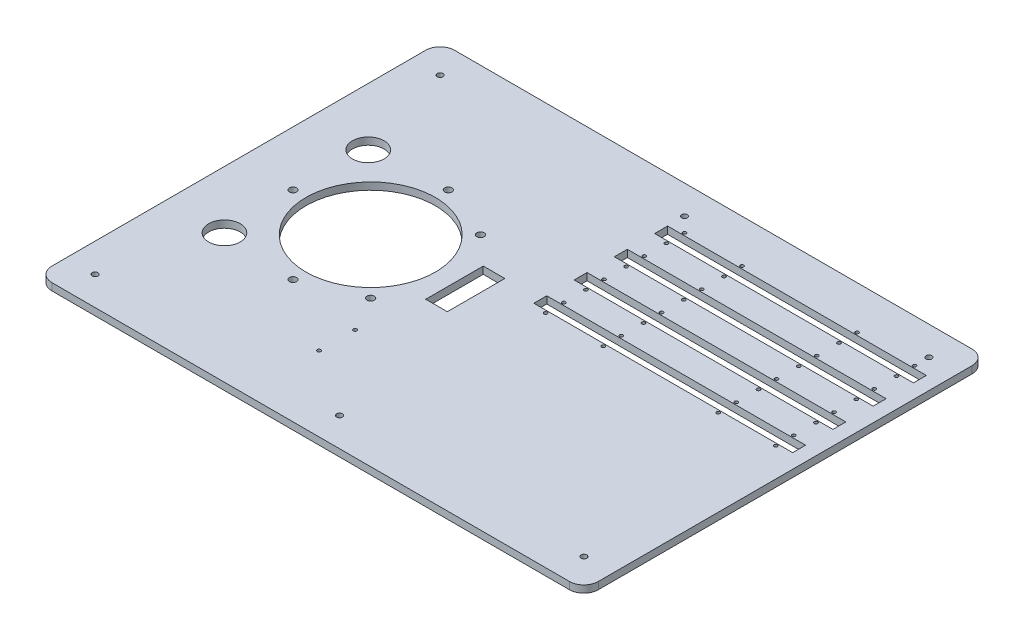
SolidWorks part; units mm, degrees
ref_plane "Front" through (0, 0, 0) normal (0, 0, 1) x (1, 0, 0)
ref_plane "Top" through (0, 0, 0) normal (0, 1, 0) x (1, 0, 0)
ref_plane "Right" through (0, 0, 0) normal (1, 0, 0) x (0, 0, -1)
sketch "Sketch1" plane through (0, 0, 0) normal (0, 1, 0) x (1, 0, 0)
  line L1 (0, 0) -> (482.6, 0)
  line L2 (0, 0) -> (0, 355.6)
  line L3 (0, 355.6) -> (482.6, 355.6)
  line L4 (482.6, 0) -> (482.6, 355.6)
  dimension "D1" = 482.6
  dimension "D2" = 355.6
extrude "Boss-Extrude1" add sketch "Sketch1" along normal blind 6.35
sketch "Sketch2" plane through (0, 6.35, 0) normal (0, 1, 0) x (1, 0, 0)
  line L0 (482.6, 355.6) -> (0, 355.6) construction
  line L1 (0, 355.6) -> (0, 0) construction
  line L2 (482.6, 0) -> (482.6, 355.6) construction
  line L3 (0, 0) -> (482.6, 0) construction
  circle A0 centre (25.4, 330.2) radius 2.55
  circle A1 centre (241.3, 330.2) radius 2.55
  circle A2 centre (457.2, 330.2) radius 2.55
  circle A3 centre (241.3, 25.4) radius 2.55
  circle A4 centre (457.2, 25.4) radius 2.55
  circle A5 centre (25.4, 25.4) radius 2.55
  dimension "D1" = 5.1
  dimension "D2" = 25.4
  dimension "D3" = 25.4
  dimension "D6" = 25.4
  dimension "D7" = 25.4
  dimension "D4" = 3
  dimension "D5" = 2
extrude "Cut-Extrude1" cut sketch "Sketch2" against normal through all
fillet "Fillet1" radius 12.7 4 edges at (0, 3.175, -355.6) (482.6, 3.175, -355.6) (482.6, 3.175, 0) (0, 3.175, 0)
sketch "Sketch3" [suppressed] plane through (0, 6.35, 0) normal (0, 1, 0) x (1, 0, 0)
  line L0 (12.7, 0) -> (469.9, 0) construction
  line L1 (482.6, 12.7) -> (482.6, 342.9) construction
  circle A0 centre (25.4, 330.2) radius 7.62
  circle A1 centre (241.3, 330.2) radius 7.62
  circle A2 centre (457.2, 330.2) radius 7.62
  circle A3 centre (241.3, 25.4) radius 7.62
  circle A4 centre (457.2, 25.4) radius 7.62
  circle A5 centre (25.4, 25.4) radius 7.62
  dimension "D1" = 15.24
  dimension "D4" = 25.4
  dimension "D5" = 25.4
  dimension "D2" = 3
  dimension "D3" = 2
extrude "Cut-Extrude2" [suppressed] cut sketch "Sketch3" against normal through all
sketch "Sketch4" [suppressed] plane through (0, 6.35, 0) normal (0, 1, 0) x (1, 0, 0)
  line L0 (482.6, 12.7) -> (482.6, 342.9) construction
  line L1 (257.81, 184.15) -> (425.45, 184.15)
  line L2 (257.81, 184.15) -> (257.81, 19.05)
  line L4 (425.45, 184.15) -> (425.45, 19.05)
  line L5 (12.7, 0) -> (469.9, 0) construction
  line L6 (257.81, 19.05) -> (425.45, 19.05)
  line L11 (469.9, 355.6) -> (12.7, 355.6) construction
  line L12 (334.01, 19.05) -> (349.25, 19.05)
  line L13 (334.01, 19.05) -> (334.01, 0)
  line L14 (334.01, 0) -> (349.25, 0)
  line L15 (349.25, 19.05) -> (349.25, 0)
  dimension "D1" = 167.64
  dimension "D2" = 165.1
  dimension "D3" = 57.15
  dimension "D4" = 76.2
  dimension "D5" = 76.2
  dimension "D6" = 171.45
extrude "Cut-Extrude3" [suppressed] cut sketch "Sketch4" against normal through all
sketch "Sketch5" plane through (0, 6.35, 0) normal (0, 1, 0) x (1, 0, 0)
  line L0 (482.6, 12.7) -> (482.6, 342.9) construction
  line L1 (469.9, 355.6) -> (12.7, 355.6) construction
  circle A0 centre (254, 317.5) radius 1.5
  circle A1 centre (304.8, 317.5) radius 1.5
  circle A3 centre (406.4, 317.5) radius 1.5
  circle A4 centre (457.2, 317.5) radius 1.5
  circle A6 centre (304.8, 301.498) radius 1.5
  circle A8 centre (406.4, 301.498) radius 1.5
  circle A9 centre (457.2, 301.498) radius 1.5
  circle A11 centre (254, 301.498) radius 1.5
  circle A12 centre (355.6, 317.5) radius 1.5 [skipped]
  circle A13 centre (355.6, 301.498) radius 1.5 [skipped]
  dimension "D1" = 3
  dimension "D4" = 228.6
  dimension "D5" = 16.002
  dimension "D6" = 38.1
  dimension "D2" = 5
  dimension "D3" = 2
extrude "Cut-Extrude4" cut sketch "Sketch5" against normal through all
sketch "Sketch6" plane through (0, 6.35, 0) normal (0, 1, 0) x (1, 0, 0)
  line L0 (482.6, 12.7) -> (482.6, 342.9) construction
  line L1 (472.44, 197.7) -> (441.44, 197.7)
  line L2 (472.44, 197.7) -> (472.44, 266.7)
  line L3 (472.44, 266.7) -> (441.44, 266.7)
  line L4 (441.44, 197.7) -> (441.44, 266.7)
  line L5 (472.44, 117.9) -> (472.44, 186.9)
  line L6 (472.44, 117.9) -> (441.44, 117.9)
  line L7 (441.44, 117.9) -> (441.44, 186.9)
  line L8 (472.44, 186.9) -> (441.44, 186.9)
  line L9 (472.44, 38.1) -> (472.44, 107.1)
  line L10 (472.44, 38.1) -> (441.44, 38.1)
  line L11 (441.44, 38.1) -> (441.44, 107.1)
  line L12 (472.44, 107.1) -> (441.44, 107.1)
  line L17 (469.9, 355.6) -> (12.7, 355.6) construction
  line L19 (472.44, -41.7) -> (472.44, 27.3) [skipped]
  line L20 (472.44, 27.3) -> (441.44, 27.3) [skipped]
  line L21 (441.44, -41.7) -> (441.44, 27.3) [skipped]
  line L22 (472.44, -41.7) -> (441.44, -41.7) [skipped]
  line L23 (12.7, 0) -> (469.9, 0) construction
  dimension "D1" = 10.16
  dimension "D2" = 69
  dimension "D3" = 31
  dimension "3.75" = 88.9
  dimension "D6" = 38.1
  dimension "D4" = 4
extrude "Cut-Extrude5" [suppressed] cut sketch "Sketch6" against normal through all
sketch "Sketch8" plane through (0, 6.35, 0) normal (0, 1, 0) x (1, 0, 0)
  line L0 (0, 342.9) -> (0, 12.7) construction
  line L1 (190.5, 203.2) -> (209.55, 203.2)
  line L2 (190.5, 203.2) -> (190.5, 152.4)
  line L3 (190.5, 152.4) -> (209.55, 152.4)
  line L4 (209.55, 203.2) -> (209.55, 152.4)
  point P6 (0, 177.8)
  point P7 (190.5, 177.8)
  dimension "D1" = 50.8
  dimension "D2" = 19.05
  dimension "D3" = 190.5
extrude "Cut-Extrude7" cut sketch "Sketch8" against normal mid plane 127
sketch "Sketch10" plane through (0, 6.35, 0) normal (0, 1, 0) x (1, 0, 0)
  line L0 (0, 342.9) -> (0, 12.7) construction
  line L1 (20.8788, 301.9425) -> (224.1042, 301.9425)
  line L2 (20.8788, 301.9425) -> (20.8788, 297.4467)
  line L3 (20.8788, 297.4467) -> (224.1042, 297.4467)
  line L4 (224.1042, 301.9425) -> (224.1042, 297.4467)
  line L5 (25.4, 297.4467) -> (29.8958, 297.4467)
  line L6 (25.4, 297.4467) -> (25.4, 58.1533)
  line L7 (25.4, 58.1533) -> (29.8958, 58.1533)
  line L8 (29.8958, 297.4467) -> (29.8958, 58.1533)
  line L13 (20.8788, 58.1533) -> (224.1042, 58.1533)
  line L14 (20.8788, 58.1533) -> (20.8788, 53.6575)
  line L15 (20.8788, 53.6575) -> (224.1042, 53.6575)
  line L16 (224.1042, 58.1533) -> (224.1042, 53.6575)
  line L17 (215.0872, 297.4467) -> (219.583, 297.4467)
  line L18 (215.0872, 297.4467) -> (215.0872, 58.1533)
  line L19 (215.0872, 58.1533) -> (219.583, 58.1533)
  line L20 (219.583, 297.4467) -> (219.583, 58.1533)
  line L22 (109.7915, 301.9425) -> (135.1915, 301.9425)
  line L23 (109.7915, 301.9425) -> (109.7915, 297.4467)
  line L24 (109.7915, 297.4467) -> (135.1915, 297.4467)
  line L25 (135.1915, 301.9425) -> (135.1915, 297.4467)
  line L26 (215.0872, 165.1) -> (219.583, 165.1)
  line L27 (215.0872, 165.1) -> (215.0872, 190.5)
  line L28 (215.0872, 190.5) -> (219.583, 190.5)
  line L29 (219.583, 165.1) -> (219.583, 190.5)
  line L30 (109.7915, 58.1533) -> (135.1915, 58.1533)
  line L31 (109.7915, 58.1533) -> (109.7915, 53.6575)
  line L32 (109.7915, 53.6575) -> (135.1915, 53.6575)
  line L33 (135.1915, 58.1533) -> (135.1915, 53.6575)
  line L34 (25.4, 165.1) -> (29.8958, 165.1)
  line L35 (25.4, 165.1) -> (25.4, 190.5)
  line L36 (25.4, 190.5) -> (29.8958, 190.5)
  line L37 (29.8958, 165.1) -> (29.8958, 190.5)
  point P16 (25.4, 177.8)
  point P19 (0, 177.8)
  point P36 (25.4, 177.8)
  point P37 (29.8958, 177.8)
  point P38 (29.8958, 177.8)
  point P39 (122.4915, 301.9425)
  point P40 (122.4915, 301.9425)
  dimension "D1" = 248.285
  dimension "D2" = 194.183
  dimension "D3" = 4.5212
  dimension "D4" = 4.5212
  dimension "D5" = 4.5212
  dimension "D6" = 4.5212
  dimension "D7" = 4.4958
  dimension "D8" = 25.4
  dimension "D9" = 25.4
extrude "Cut-Extrude9" cut sketch "Sketch10" against normal blind 6.35 contours L31 L13 L7 L14 L15 | L34 L6 L7 L8 | L23 L1 L2 L3 | L1 L25 L3 L4 | L18 L28 L20 L3 | L26 L18 L13 L20 | L13 L33 L15 L16
sketch "Sketch11" plane through (0, 6.35, 0) normal (0, 1, 0) x (1, 0, 0)
  line L0 (469.9, 355.6) -> (12.7, 355.6) construction
  line L1 (162.2, 88.9) -> (203.2, 88.9)
  line L2 (162.2, 88.9) -> (162.2, 74.9)
  line L3 (162.2, 74.9) -> (203.2, 74.9)
  line L4 (203.2, 88.9) -> (203.2, 74.9)
  line L5 (482.6, 12.7) -> (482.6, 342.9) construction
  dimension "D3" = 266.7
  dimension "D1" = 41
  dimension "D2" = 14
  dimension "D4" = 279.4
extrude "Cut-Extrude10" [suppressed] cut sketch "Sketch11" against normal through all
sketch "Sketch12" plane through (0, 6.35, 0) normal (0, 1, 0) x (1, 0, 0)
  line L0 (0, 342.9) -> (0, 12.7) construction
  line L1 (50.8, 241.3) -> (50.8, 114.3) construction
  line L3 (63.6988, 246.7424) -> (76.3988, 246.7424)
  line L4 (63.6988, 246.7424) -> (63.6988, 235.8576)
  line L5 (63.6988, 235.8576) -> (76.3988, 235.8576)
  line L6 (76.3988, 246.7424) -> (76.3988, 235.8576)
  line L7 (63.6988, 119.7424) -> (76.3988, 119.7424)
  line L8 (63.6988, 119.7424) -> (63.6988, 108.8576)
  line L9 (63.6988, 108.8576) -> (76.3988, 108.8576)
  line L10 (76.3988, 119.7424) -> (76.3988, 108.8576)
  circle A0 centre (50.8, 241.3) radius 14
  circle A1 centre (50.8, 114.3) radius 14
  point P2 (50.8, 177.8)
  point P5 (0, 177.8)
  point P17 (63.6988, 241.3)
  point P18 (63.6988, 114.3)
  dimension "D1" = 28
  dimension "D2" = 127
  dimension "D3" = 50.8
  dimension "D4" = 12.7
extrude "Cut-Extrude11" cut sketch "Sketch12" against normal mid plane 127
sketch "Sketch13" plane through (0, 6.35, 0) normal (0, 1, 0) x (1, 0, 0)
  line L1 (11.0927, 314.0237) -> (231.0973, 314.0237)
  line L2 (11.0927, 314.0237) -> (11.0927, 49.9586)
  line L3 (11.0927, 49.9586) -> (231.0973, 49.9586)
  line L4 (231.0973, 314.0237) -> (231.0973, 49.9586)
extrude "Boss-Extrude2" add sketch "Sketch13" against normal blind 6.35
sketch "Sketch14" plane through (0, 6.35, 0) normal (0, 1, 0) x (1, 0, 0)
  line L0 (29.8958, 297.4467) -> (29.8958, 58.1533) construction
  line L4 (109.7915, 53.6575) -> (135.1915, 53.6575) construction
  line L5 (0, 342.9) -> (0, 12.7) construction
  circle A0 centre (116.84, 177.8) radius 57.2135
  point P4 (29.8958, 177.8)
  dimension "D1" = 116.84
  dimension "D2" = 114.427
extrude "Cut-Extrude12" [suppressed] cut sketch "Sketch14" against normal through all
sketch "Sketch15" plane through (0, 6.35, 0) normal (0, 1, 0) x (1, 0, 0)
  line L0 (50.8, 241.3) -> (50.8, 114.3) construction
  line L1 (0, 342.9) -> (0, 12.7) construction
  circle A0 centre (50.8, 241.3) radius 13.97
  circle A1 centre (50.8, 114.3) radius 13.97
  point P6 (0, 177.8)
  point P7 (50.8, 177.8)
  dimension "D1" = 27.94
  dimension "D2" = 127
  dimension "D3" = 50.8
extrude "Cut-Extrude13" cut sketch "Sketch15" against normal through all
sketch "Sketch16" [suppressed] plane through (0, 6.35, 0) normal (0, 1, 0) x (1, 0, 0)
  line L1 (432.299, 273.4014) -> (473.1365, 273.4014)
  line L2 (432.299, 273.4014) -> (432.299, 196.3719)
  line L3 (432.299, 196.3719) -> (473.1365, 196.3719)
  line L4 (473.1365, 273.4014) -> (473.1365, 196.3719)
extrude "Boss-Extrude3" [suppressed] add sketch "Sketch16" against normal up to surface (6.35 mm away)
pattern_linear "LPattern1" count 4 spacing 35.56 along (0, 0, 1) of "Cut-Extrude4"
sketch "Sketch17" plane through (0, 6.35, 0) normal (0, 1, 0) x (1, 0, 0)
  line L1 (241.3, 315.214) -> (469.9, 315.214)
  line L2 (241.3, 315.214) -> (241.3, 303.784)
  line L3 (241.3, 303.784) -> (469.9, 303.784)
  line L4 (469.9, 315.214) -> (469.9, 303.784)
  line L5 (241.3, 279.654) -> (241.3, 268.224)
  line L6 (241.3, 279.654) -> (469.9, 279.654)
  line L7 (469.9, 279.654) -> (469.9, 268.224)
  line L8 (241.3, 268.224) -> (469.9, 268.224)
  line L9 (241.3, 244.094) -> (241.3, 232.664)
  line L10 (241.3, 244.094) -> (469.9, 244.094)
  line L11 (469.9, 244.094) -> (469.9, 232.664)
  line L12 (241.3, 232.664) -> (469.9, 232.664)
  line L13 (241.3, 208.534) -> (241.3, 197.104)
  line L14 (241.3, 208.534) -> (469.9, 208.534)
  line L15 (469.9, 208.534) -> (469.9, 197.104)
  line L16 (241.3, 197.104) -> (469.9, 197.104)
  line L17 (254, 317.5) -> (254, 301.498) construction
  line L18 (254, 210.82) -> (254, 194.818) construction
  line L19 (482.6, 12.7) -> (482.6, 342.9) construction
  point P20 (241.3, 202.819)
  point P21 (254, 202.819)
  point P24 (241.3, 309.499)
  point P25 (254, 309.499)
  dimension "D4" = 12.7
  dimension "D1" = 11.43
  dimension "D2" = 228.6
  dimension "D3" = 4
extrude "Cut-Extrude14" cut sketch "Sketch17" against normal through all
sketch "Sketch18" plane through (0, 6.35, 0) normal (0, 1, 0) x (1, 0, 0)
  line L0 (0, 342.9) -> (0, 12.7) construction
  line L1 (190.5, 203.2) -> (209.55, 203.2)
  line L2 (190.5, 203.2) -> (190.5, 152.4)
  line L3 (190.5, 152.4) -> (209.55, 152.4)
  line L4 (209.55, 203.2) -> (209.55, 152.4)
  point P6 (0, 177.8)
  point P7 (190.5, 177.8)
  dimension "D1" = 19.05
  dimension "D2" = 50.8
  dimension "D3" = 190.5
extrude "Cut-Extrude15" cut sketch "Sketch18" against normal through all
sketch "Sketch19" plane through (0, 6.35, 0) normal (0, 1, 0) x (1, 0, 0)
  line L4 (0, 342.9) -> (0, 12.7) construction
  line L5 (12.7, 0) -> (469.9, 0) construction
  circle A0 centre (182.7, 97.775) radius 1.5875
  circle A1 centre (182.7, 66.025) radius 1.5875
  dimension "D1" = 3.175
  dimension "D2" = 31.75
  dimension "D3" = 182.7
  dimension "D4" = 66.025
extrude "Cut-Extrude16" cut sketch "Sketch19" against normal through all
sketch "Sketch20" plane through (0, 6.35, 0) normal (0, 1, 0) x (1, 0, 0)
  line L0 (0, 342.9) -> (0, 12.7) construction
  circle A0 centre (116.84, 177.4261) radius 57.15
  dimension "D1" = 114.3
  dimension "D2" = 116.84
extrude "Cut-Extrude17" cut sketch "Sketch20" against normal through all
sketch "Sketch21" plane through (0, 6.35, 0) normal (0, 1, 0) x (1, 0, 0)
  circle A0 centre (116.84, 177.4261) radius 68.58 construction
  circle A1 centre (116.84, 177.4261) radius 57.15 construction
  circle A2 centre (116.84, 246.0061) radius 3.175
  circle A3 centre (48.26, 177.4261) radius 3.175
  circle A4 centre (116.84, 108.8461) radius 3.175
  circle A6 centre (165.3334, 128.9327) radius 3.175
  circle A7 centre (165.3334, 225.9195) radius 3.175
  dimension "D1" = 137.16
  dimension "D2" = 6.35
  dimension "D3" = 45
  dimension "D4" = 45
extrude "Cut-Extrude18" cut sketch "Sketch21" against normal through all
